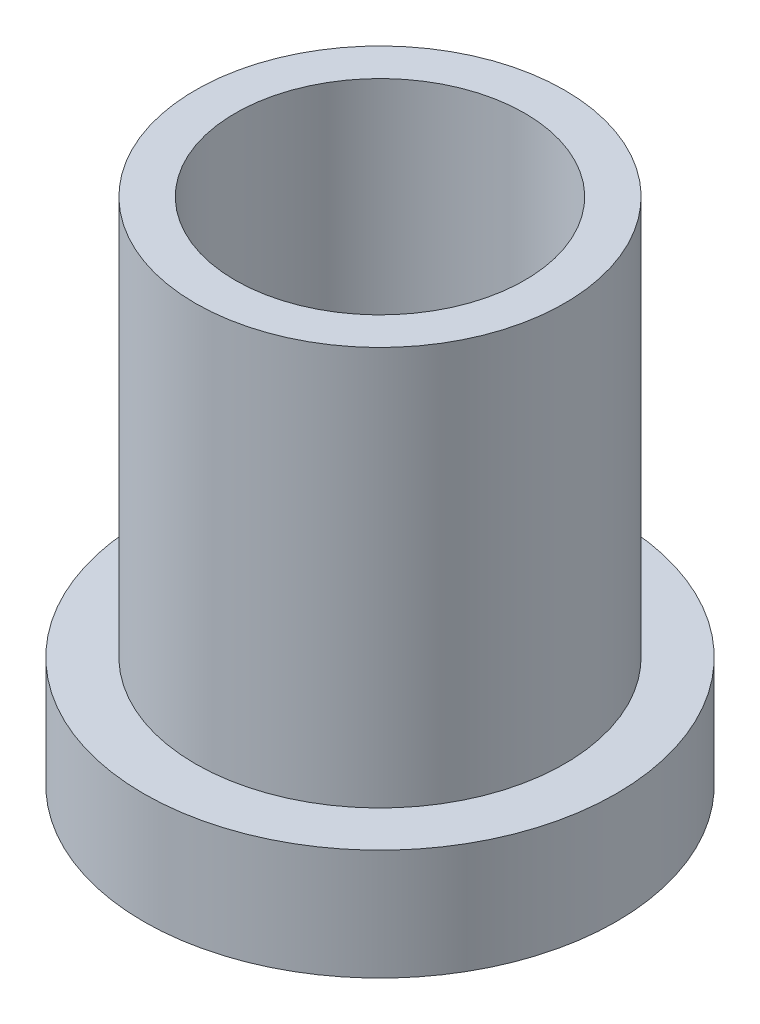
SolidWorks part; units mm, degrees
material "PET"
ref_plane "Front Plane" through (0, 0, 0) normal (0, 0, 1) x (1, 0, 0)
ref_plane "Top Plane" through (0, 0, 0) normal (0, 1, 0) x (1, 0, 0)
ref_plane "Right Plane" through (0, 0, 0) normal (1, 0, 0) x (0, 0, -1)
sketch "Sketch1" plane through (0, 0, 0) normal (0, 1, 0) x (1, 0, 0)
  circle A0 centre (0, 0) radius 3.175
  circle A1 centre (0, 0) radius 2.4892
  dimension "D1" = 6.35
  dimension "D2" = 4.9784
extrude "Boss-Extrude1" add sketch "Sketch1" along normal blind 6.858
sketch "Sketch2" plane through (0, 0, 0) normal (0, -1, 0) x (1, 0, 0)
  circle A0 centre (0, 0) radius 4.064
extrude "Boss-Extrude2" add sketch "Sketch2" along normal blind 1.905
sketch "Sketch3" plane through (0, -1.905, 0) normal (0, -1, 0) x (1, 0, 0)
  circle A0 centre (0, 0) radius 2.4892
  dimension "D1" = 4.9784
extrude "Cut-Extrude1" cut sketch "Sketch3" against normal through all
